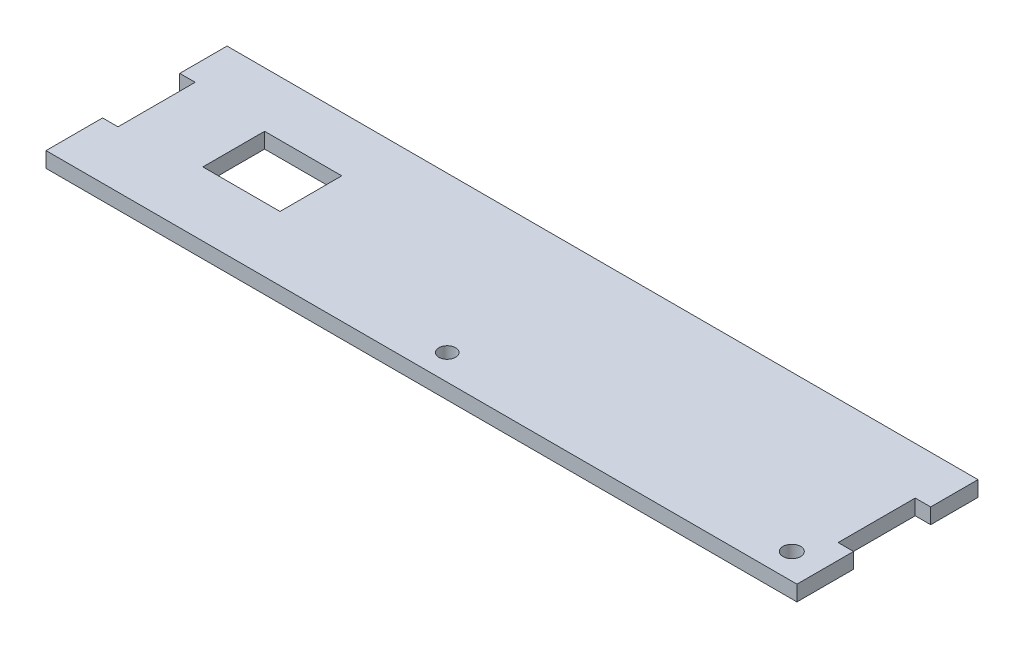
SolidWorks part; units mm, degrees
ref_plane "Front Plane" through (0, 0, 0) normal (0, 0, 1) x (1, 0, 0)
ref_plane "Top Plane" through (0, 0, 0) normal (0, 1, 0) x (1, 0, 0)
ref_plane "Right Plane" through (0, 0, 0) normal (1, 0, 0) x (0, 0, -1)
other "Configuration Table"
sketch "Sketch1" plane through (0, 0, 0) normal (0, 1, 0) x (1, 0, 0)
  line L1 (73, -30.5) -> (-73, -30.5)
  line L2 (73, -30.5) -> (73, 30.5)
  line L3 (73, 30.5) -> (-73, 30.5)
  line L4 (-73, -30.5) -> (-73, 30.5)
  line L5 (73, -30.5) -> (-73, 30.5) construction
  line L6 (73, 30.5) -> (-73, -30.5) construction
  point P0 (0, 0)
  dimension "D1" = 61
  dimension "D2" = 146
extrude "Boss-Extrude1" add sketch "Sketch1" along normal blind 3
sketch "Sketch2" plane through (0, 3, 0) normal (0, 1, 0) x (1, 0, 0)
  line L0 (-73, 30.5) -> (-73, -30.5) construction
  line L1 (73, -30.5) -> (73, 30.5) construction
  line L2 (-73, -30.5) -> (73, -30.5) construction
  line L7 (-70, -4.5) -> (-70, -19.5)
  line L8 (-70, -19.5) -> (-73, -19.5)
  line L9 (-73, -19.5) -> (-73, -4.5)
  line L10 (-73, -4.5) -> (-70, -4.5)
  line L11 (73, 20.5) -> (70, 20.5)
  line L12 (70, 20.5) -> (70, 5.5)
  line L13 (70, 5.5) -> (73, 5.5)
  line L14 (70, -4.5) -> (70, -19.5)
  line L15 (70, -19.5) -> (73, -19.5)
  line L16 (73, -19.5) -> (73, -4.5)
  line L17 (73, -4.5) -> (70, -4.5)
  line L18 (73, 20.5) -> (73, 5.5)
  line L28 (-73, 20.5) -> (-70, 20.5)
  line L29 (-70, 20.5) -> (-70, 5.5)
  line L30 (-70, 5.5) -> (-73, 5.5)
  line L31 (-73, 5.5) -> (-73, 20.5)
  line L32 (73, 30.5) -> (-73, 30.5) construction
  line L33 (-40, -18) -> (-55, -18)
  line L34 (-40, -18) -> (-40, -6)
  line L35 (-40, -6) -> (-55, -6)
  line L36 (-55, -18) -> (-55, -6)
  line L37 (-40, -18) -> (-55, -6) construction
  line L38 (-40, -6) -> (-55, -18) construction
  line L39 (-43, 30.5) -> (-13, 30.5)
  line L40 (-43, 30.5) -> (-43, 27.5)
  line L41 (-43, 27.5) -> (-13, 27.5)
  line L42 (-13, 30.5) -> (-13, 27.5)
  line L44 (13, 30.5) -> (43, 30.5)
  line L45 (13, 30.5) -> (13, 27.5)
  line L46 (13, 27.5) -> (43, 27.5)
  line L47 (43, 30.5) -> (43, 27.5)
  circle A2 centre (0, -25.5) radius 1.6214
  circle A3 centre (67, -25.5) radius 1.7186
  point P8 (-47.5, -12)
  dimension "D2" = 11
  dimension "D3" = 15
  dimension "D4" = 10
  dimension "D5" = 3
  dimension "D6" = 11
  dimension "D7" = 15
  dimension "D8" = 73
  dimension "D9" = 5
  dimension "D10" = 5
  dimension "D11" = 6
  dimension "D12" = 15
  dimension "D13" = 10
  dimension "D14" = 3
  dimension "D15" = 30
  dimension "D16" = 30
  dimension "D17" = 12
  dimension "D18" = 15
  dimension "D19" = 12.5
  dimension "D20" = 25.5
  dimension "D21" = 30
  dimension "D22" = 30
extrude "Cut-Extrude1" cut sketch "Sketch2" against normal blind 10
sketch "Sketch3" plane through (0, 3, 0) normal (0, 1, 0) x (1, 0, 0)
  line L0 (-73, 4.7) -> (73, 4.7)
  line L1 (-73, 5.5) -> (-73, -4.5) construction
  line L2 (73, -4.5) -> (73, 5.5) construction
  line L3 (73, 4.7) -> (73, 30.5)
  line L4 (73, 30.5) -> (-73, 30.5)
  line L5 (-73, 30.5) -> (-73, 4.7)
  dimension "D1" = 0.8
extrude "Cut-Extrude2" cut sketch "Sketch3" against normal blind 10
